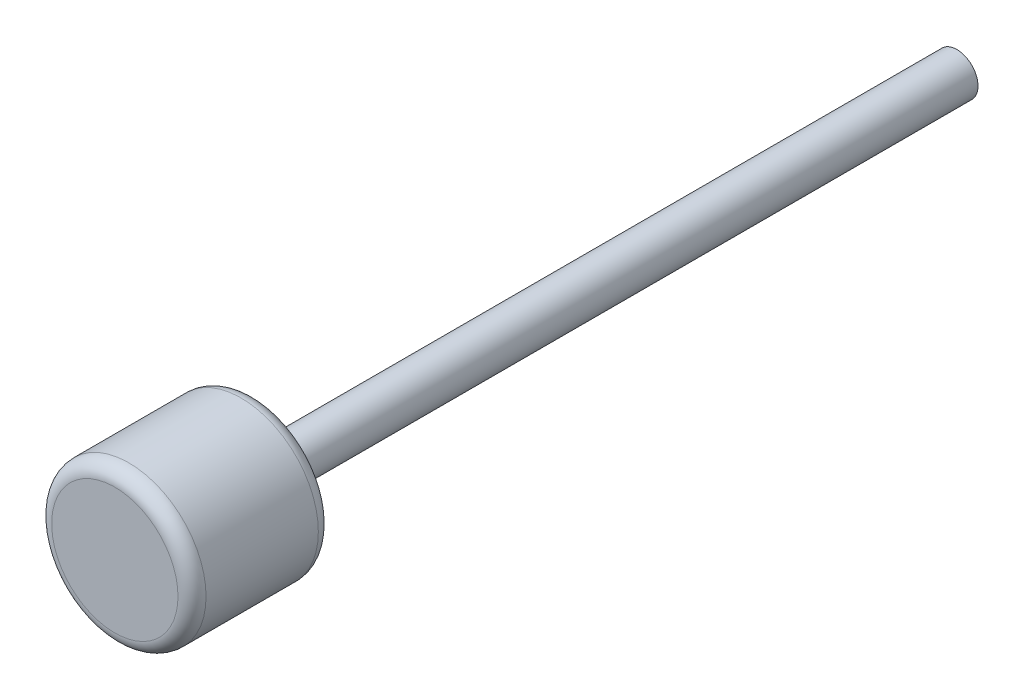
SolidWorks part; units mm, degrees
ref_plane "Front Plane" through (0, 0, 0) normal (0, 0, 1) x (1, 0, 0)
ref_plane "Top Plane" through (0, 0, 0) normal (0, 1, 0) x (1, 0, 0)
ref_plane "Right Plane" through (0, 0, 0) normal (1, 0, 0) x (0, 0, -1)
sketch "Sketch1" plane through (0, 0, 0) normal (0, 0, 1) x (1, 0, 0)
  circle A0 centre (0, 12.0208) radius 1.5
extrude "Boss-Extrude1" add sketch "Sketch1" along normal blind 50
sketch "Sketch2" plane through (0, 0, 50) normal (0, 0, 1) x (1, 0, 0)
  line L0 (0, 12.0208) -> (0, 11.1116) construction
  circle A0 centre (0, 12.0208) radius 5.5
extrude "Boss-Extrude2" add sketch "Sketch2" along normal blind 10
fillet "Fillet1" radius 1 2 edges at (5.5, 12.0208, 50) (5.5, 12.0208, 60)
